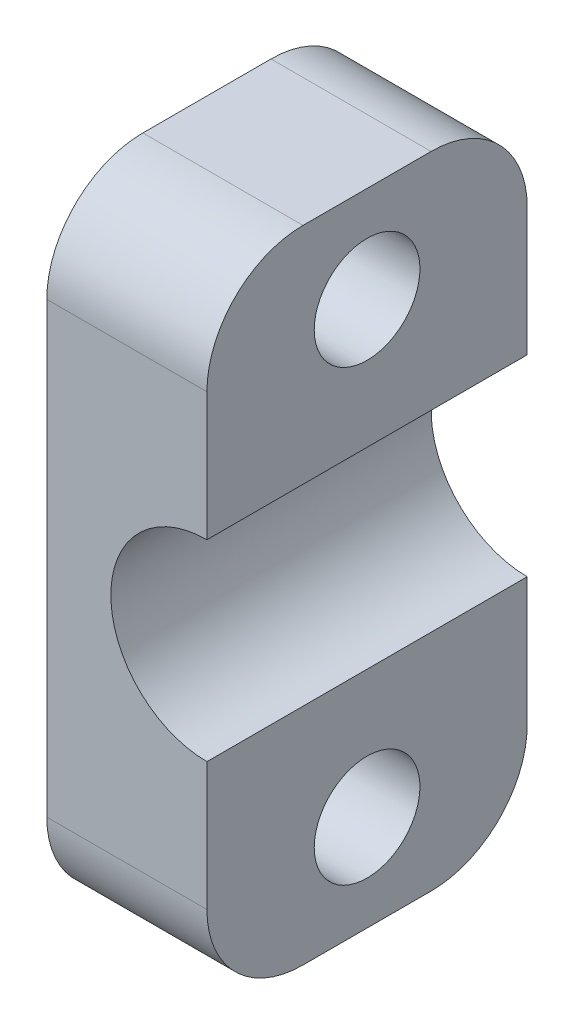
SolidWorks part; units mm, degrees
ref_plane "Front Plane" through (0, 0, 0) normal (0, 0, 1) x (1, 0, 0)
ref_plane "Top Plane" through (0, 0, 0) normal (0, 1, 0) x (1, 0, 0)
ref_plane "Right Plane" through (0, 0, 0) normal (1, 0, 0) x (0, 0, -1)
sketch "草圖1" plane through (0, 0, 0) normal (0, 0, 1) x (1, 0, 0)
  line L1 (5, -10) -> (-5, -10)
  line L2 (5, -10) -> (5, 10)
  line L3 (5, 10) -> (-5, 10)
  line L4 (-5, -10) -> (-5, 10)
  line L5 (5, -10) -> (-5, 10) construction
  line L6 (5, 10) -> (-5, -10) construction
  circle A0 centre (0, 0) radius 3
  point P0 (0, 0)
  dimension "D3" = 6
  dimension "D1" = 10
  dimension "D2" = 20
extrude "填料-伸長1" add sketch "草圖1" along normal blind 10
sketch "草圖2" plane through (-5, 0, 0) normal (-1, 0, 0) x (0, 0, 1)
  line L0 (0, 10) -> (0, -10) construction
  line L1 (10, 10) -> (0, 10) construction
  line L2 (10, -10) -> (0, -10) construction
  circle A0 centre (5, 7) radius 1.65
  circle A1 centre (5, -7) radius 1.65
  point P4 (0, 0)
  dimension "D1" = 3.3
  dimension "D2" = 5
  dimension "D3" = 3
  dimension "D4" = 3
extrude "除料-伸長1" cut sketch "草圖2" against normal through all
sketch "草圖3" plane through (0, 0, 10) normal (0, 0, 1) x (1, 0, 0)
  line L0 (5, 10) -> (-5, 10) construction
  line L1 (0, 10) -> (12.8527, 10)
  line L2 (0, 10) -> (0, -10.2796)
  line L3 (0, -10.2796) -> (12.8527, -10.2796)
  line L4 (12.8527, 10) -> (12.8527, -10.2796)
extrude "除料-伸長2" cut sketch "草圖3" against normal through all
fillet "圓角1" radius 3 4 edges at (-2.5, -10, 10) (-2.5, -10, 0) (-2.5, 10, 0) (-2.5, 10, 10)
